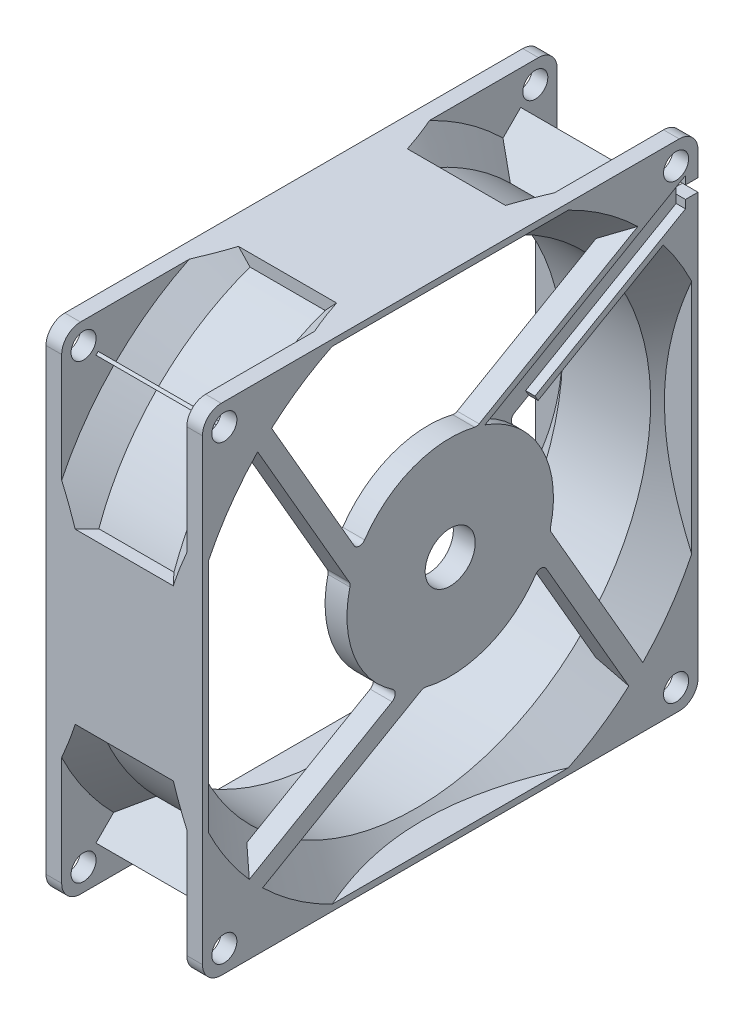
SolidWorks part; units mm, degrees
ref_plane "Front Plane" through (0, 0, 0) normal (0, 0, 1) x (1, 0, 0)
ref_plane "Top Plane" through (0, 0, 0) normal (0, 1, 0) x (1, 0, 0)
ref_plane "Right Plane" through (0, 0, 0) normal (1, 0, 0) x (0, 0, -1)
sketch "Sketch1" plane through (0, 0, 0) normal (0, 0, 1) x (1, 0, 0)
  line L0 (-10, 56) -> (-10, 44)
  line L1 (-10, 44) -> (-6, 40)
  line L2 (-6, 40) -> (6, 40)
  line L3 (6, 40) -> (10, 44)
  line L4 (10, 44) -> (10, 56)
  line L5 (-12.5, 56) -> (-12.5, 42.9645)
  line L6 (-12.5, 42.9645) -> (-7.0355, 37.5)
  line L7 (-7.0355, 37.5) -> (7.0355, 37.5)
  line L8 (7.0355, 37.5) -> (12.5, 42.9645)
  line L9 (12.5, 42.9645) -> (12.5, 56)
  line L10 (-12.5, 56) -> (-10, 56)
  line L11 (10, 56) -> (12.5, 56)
  line L12 (-12.5, 0) -> (13.9887, 0) construction
  point P8 (0, 40)
  dimension "D1" = 12
  dimension "D2" = 4
  dimension "D3" = 12
  dimension "D4" = 45
  dimension "D5" = 40
  dimension "D6" = 45
  dimension "D7" = 2.5
revolve "Revolve1" add sketch "Sketch1" angle 360 about L12
sketch "Sketch2" plane through (12.5, 0, 0) normal (1, 0, 0) x (0, 0, -1)
  line L1 (-39.598, 39.598) -> (39.598, 39.598)
  line L2 (-39.598, 39.598) -> (-39.598, -39.598)
  line L3 (-39.598, -39.598) -> (39.598, -39.598)
  line L4 (39.598, 39.598) -> (39.598, -39.598)
  line L5 (-39.598, 39.598) -> (39.598, -39.598) construction
  line L6 (-39.598, -39.598) -> (39.598, 39.598) construction
  circle A0 centre (0, 0) radius 56 construction
  point P0 (0, 0)
extrude "Cut-Extrude1" cut sketch "Sketch2" against normal through all flip side to cut
sketch "Sketch3" plane through (12.5, 0, 0) normal (1, 0, 0) x (0, 0, -1)
  line L0 (-16.6717, 39.598) -> (-39.598, 39.598) construction
  line L1 (-18.8717, 39.598) -> (18.8717, 39.598)
  line L2 (-18.8717, 39.598) -> (-18.8717, 38.598)
  line L3 (-18.8717, 38.598) -> (18.8717, 38.598)
  line L4 (18.8717, 39.598) -> (18.8717, 38.598)
  arc A0 (39.598, 16.6717) -> (16.6717, 39.598) centre (0, 0) ccw construction
  arc A2 (-16.6717, 39.598) -> (-39.598, 16.6717) centre (0, 0) ccw construction
  dimension "D1" = 1
extrude "Boss-Extrude1" add sketch "Sketch3" against normal up to body separate body
pattern_circular "CirPattern1" count 4 over 360 about axis through (0, 0, 0) along (1, 0, 0) of "Boss-Extrude1"
mirror "Mirror1" about plane through (0, 0, 0) normal (1, 0, 0) of "CirPattern1", "Boss-Extrude1"
sketch "Sketch4" plane through (0, 0, 0) normal (1, 0, 0) x (0, 0, -1)
  line L0 (0, 0) -> (39.598, 39.598) construction
  line L1 (33.7643, 34.1179) -> (26.3391, 26.6927)
  line L2 (33.7643, 34.1179) -> (34.1179, 33.7643)
  line L3 (26.3391, 26.6927) -> (26.6927, 26.3391)
  line L4 (34.1179, 33.7643) -> (26.6927, 26.3391)
  circle A0 centre (0, 0) radius 37.5 construction
  point P4 (26.5159, 26.5159)
  point P14 (33.9411, 33.9411)
  dimension "D1" = 0.5
  dimension "D2" = 48
extrude "Boss-Extrude2" add sketch "Sketch4" along normal up to body and the other way up to body separate body
pattern_circular "CirPattern2" count 4 over 360 about axis through (0, 0, 0) along (1, 0, 0) of "Boss-Extrude2"
sketch "Sketch5" plane through (12.5, 0, 0) normal (1, 0, 0) x (0, 0, -1)
  line L0 (-39.598, -39.598) -> (39.598, -39.598) construction
  line L1 (39.598, -39.598) -> (39.598, 39.598) construction
  circle A0 centre (36.098, -36.098) radius 2
  dimension "D1" = 4
  dimension "D2" = 3.5
  dimension "D3" = 3.5
extrude "Cut-Extrude2" cut sketch "Sketch5" against normal through all separate body
pattern_circular "CirPattern3" count 4 over 360 about axis through (0, 0, 0) along (1, 0, 0) of "Cut-Extrude2"
fillet "Fillet1" radius 3 8 edges at (-11.25, 39.598, -39.598) (11.25, 39.598, -39.598) (-11.25, -39.598, -39.598) (11.25, -39.598, -39.598) (-11.25, -39.598, 39.598) (11.25, -39.598, 39.598) (-11.25, 39.598, 39.598) (11.25, 39.598, 39.598)
sketch "Sketch6" plane through (12.5, 0, 0) normal (1, 0, 0) x (0, 0, -1)
  line L0 (0, 39.598) -> (0, -39.598) construction
  line L1 (36.598, 39.598) -> (-36.598, 39.598) construction
  line L2 (-36.598, -39.598) -> (36.598, -39.598) construction
  line L3 (-39.598, 0) -> (39.598, 0) construction
  line L4 (-39.598, 36.598) -> (-39.598, -36.598) construction
  line L5 (39.598, -36.598) -> (39.598, 36.598) construction
  line L6 (29.9765, 30.7791) -> (4.2705, 15.9378)
  line L7 (10.5865, 12.6561) -> (34.0496, 26.2025)
  line L8 (0, 0) -> (4.2705, 15.9378) construction
  line L9 (-14.5262, 7.8256) -> (-28.5466, 32.1097)
  line L10 (-30.7791, 29.9765) -> (-15.9378, 4.2705)
  line L11 (0, 0) -> (-15.9378, 4.2705) construction
  line L12 (29.9765, 30.7791) -> (4.2705, 15.9378) [skipped]
  line L13 (7.8256, 14.5262) -> (32.1097, 28.5466) [skipped]
  line L14 (30.7791, -29.9765) -> (15.9378, -4.2705)
  line L15 (14.5262, -7.8256) -> (28.5466, -32.1097)
  line L16 (-29.9765, -30.7791) -> (-4.2705, -15.9378)
  line L17 (-7.8256, -14.5262) -> (-32.1097, -28.5466)
  arc A0 (-15.9378, 4.2705) -> (-7.8256, -14.5262) centre (0, 0) ccw
  arc A1 (18.8717, -38.598) -> (38.598, -18.8717) centre (0, 0) ccw construction
  arc A2 (-38.598, -18.8717) -> (-18.8717, -38.598) centre (0, 0) ccw construction
  arc A3 (-18.8717, 38.598) -> (-38.598, 18.8717) centre (0, 0) ccw construction
  arc A4 (38.598, 18.8717) -> (18.8717, 38.598) centre (0, 0) ccw construction
  arc A5 (28.5466, -32.1097) -> (30.7791, -29.9765) centre (0, 0) ccw
  arc A6 (-32.1097, -28.5466) -> (-29.9765, -30.7791) centre (0, 0) ccw
  arc A7 (-28.5466, 32.1097) -> (-30.7791, 29.9765) centre (0, 0) ccw
  arc A8 (34.0496, 26.2025) -> (29.9765, 30.7791) centre (0, 0) ccw
  arc A9 (4.2705, 15.9378) -> (-14.5262, 7.8256) centre (0, 0) ccw
  arc A10 (15.9378, -4.2705) -> (10.5865, 12.6561) centre (0, 0) ccw
  arc A11 (-4.2705, -15.9378) -> (14.5262, -7.8256) centre (0, 0) ccw
  circle A12 centre (0, 0) radius 4
  point P50 (0, 0)
  dimension "D1" = 33
  dimension "D9" = 8
  dimension "D2" = 6
  dimension "D3" = 30
  dimension "D4" = 15
  dimension "D5" = 3
  dimension "D6" = 30
  dimension "D7" = 15
  dimension "D8" = 4
extrude "Boss-Extrude3" add sketch "Sketch6" against normal blind 3.5
sketch "Sketch7" plane through (12.5, 0, 0) normal (1, 0, 0) x (0, 0, -1)
  line L0 (5.568, 15.5322) -> (37.598, 34.0247)
  line L1 (37.598, 34.0247) -> (37.598, 32.7153)
  line L2 (37.598, 32.7153) -> (39.598, 32.7153)
  line L3 (39.598, -36.598) -> (39.598, 36.598) construction
  line L4 (39.598, 32.7153) -> (39.598, 30.7153)
  line L5 (39.598, 30.7153) -> (37.598, 30.7153)
  line L6 (37.598, 30.7153) -> (37.598, 29.4059)
  line L7 (37.598, 29.4059) -> (13.5506, 15.5221)
  line L8 (13.5506, 15.5221) -> (14.0506, 14.6561)
  line L10 (10.5865, 12.6561) -> (34.0496, 26.2025) construction
  line L11 (14.0506, 14.6561) -> (10.5865, 12.6561)
  line L12 (29.9765, 30.7791) -> (4.2705, 15.9378) construction
  arc A0 (5.568, 15.5322) -> (10.5865, 12.6561) centre (0, 0) cw
  point P17 (10.402, 12.6561)
  dimension "D1" = 4
  dimension "D2" = 1
  dimension "D3" = 1
  dimension "D4" = 2
  dimension "D5" = 2
extrude "Cut-Extrude3" cut sketch "Sketch7" against normal blind 1.5
sketch "Sketch8" plane through (11, 0, 0) normal (1, 0, 0) x (0, 0, -1)
  line L1 (37.598, 32.7153) -> (39.598, 32.7153)
  line L2 (37.598, 32.7153) -> (37.598, 30.7153)
  line L3 (37.598, 30.7153) -> (39.598, 30.7153)
  line L4 (39.598, 32.7153) -> (39.598, 30.7153)
extrude "Cut-Extrude4" cut sketch "Sketch8" against normal up to next
fillet "Fillet2" radius 1 8 edges at (10.75, -7.8256, -14.5262) (10.75, -4.2705, -15.9378) (10, 12.6561, -10.5865) (10.75, 15.9378, -4.2705) (10.75, 7.8256, 14.5262) (10.75, 4.2705, 15.9378) (10.75, -14.5262, 7.8256) (10.75, -15.9378, 4.2705)
sketch "Sketch9" plane through (0, 0, -39.598) normal (0, 0, -1) x (-1, 0, 0)
  line L1 (-10, 13.5) -> (10, 13.5)
  line L2 (-10, 13.5) -> (-10, -13.5)
  line L3 (-10, -13.5) -> (10, -13.5)
  line L4 (10, 13.5) -> (10, -13.5)
  line L8 (-10, 19.1833) -> (-10, 30.9354) construction
  line L9 (10, 30.9354) -> (10, 19.1833) construction
  point P8 (10, 0)
  dimension "D1" = 27
extrude "Boss-Extrude4" add sketch "Sketch9" against normal up to body separate body
pattern_circular "CirPattern4" count 4 over 360 about axis through (0, 0, 0) along (1, 0, 0) of "Boss-Extrude4"
